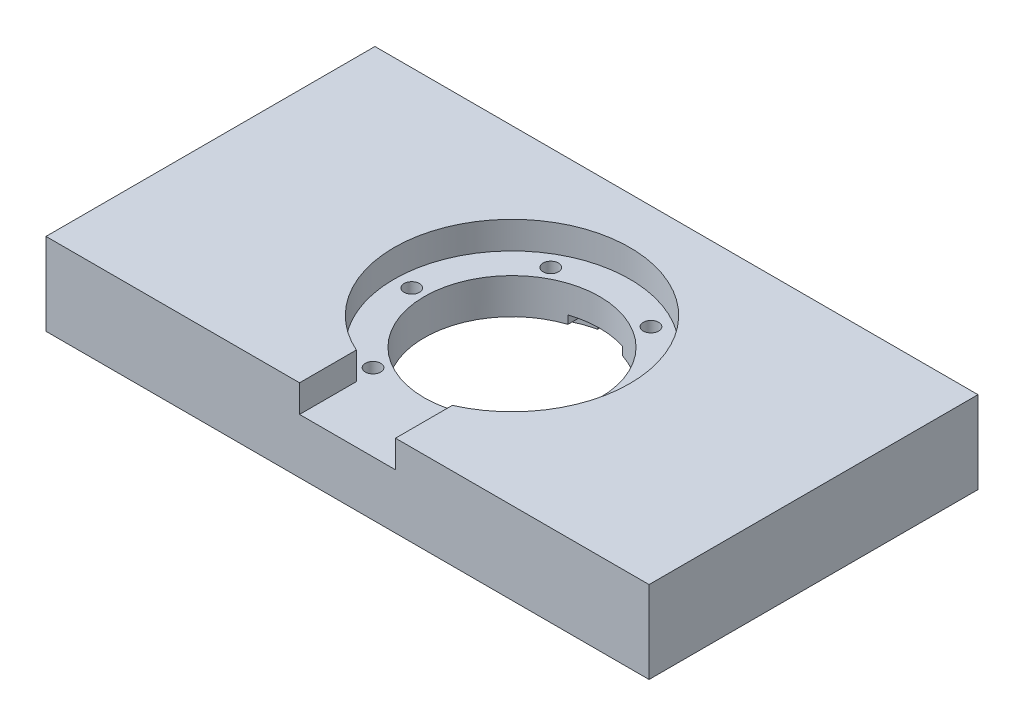
SolidWorks part; units mm, degrees
ref_plane "Front Plane" through (0, 0, 0) normal (0, 0, 1) x (1, 0, 0)
ref_plane "Top Plane" through (0, 0, 0) normal (0, 1, 0) x (1, 0, 0)
ref_plane "Right Plane" through (0, 0, 0) normal (1, 0, 0) x (0, 0, -1)
sketch "Sketch1" plane through (0, 0, 0) normal (0, 1, 0) x (1, 0, 0)
  line L1 (110, -60) -> (-110, -60)
  line L2 (110, -60) -> (110, 60)
  line L3 (110, 60) -> (-110, 60)
  line L4 (-110, -60) -> (-110, 60)
  line L5 (110, -60) -> (-110, 60) construction
  line L6 (110, 60) -> (-110, -60) construction
  circle A0 centre (0, 0) radius 43
  dimension "D1" = 86
  dimension "D2" = 120
  dimension "D3" = 220
extrude "Boss-Extrude1" add sketch "Sketch1" along normal blind 10
sketch "Sketch2" plane through (0, 0, 0) normal (0, -1, 0) x (1, 0, 0)
  line L1 (-110, 60) -> (110, 60)
  line L2 (-110, 60) -> (-110, -60)
  line L3 (-110, -60) -> (110, -60)
  line L4 (110, 60) -> (110, -60)
  circle A0 centre (18.1221, 32.2581) radius 2.8
  circle A1 centre (36.9974, 0.4348) radius 2.8
  circle A2 centre (18.8753, -31.8233) radius 2.8
  circle A3 centre (-18.1221, -32.2581) radius 2.8
  circle A4 centre (-36.9974, -0.4348) radius 2.8
  circle A5 centre (-18.8753, 31.8233) radius 2.8
  point P21 (0, 0)
  dimension "D1" = 5.6
  dimension "D2" = 37
  dimension "D3" = 6
extrude "Boss-Extrude2" add sketch "Sketch2" along normal blind 20
sketch "Sketch3" plane through (0, 0, 60) normal (0, 0, 1) x (1, 0, 0)
  line L0 (-110, 10) -> (110, 10) construction
  line L1 (-17.5, 0) -> (17.5, 0)
  line L2 (-17.5, 0) -> (-17.5, 10)
  line L3 (-17.5, 10) -> (17.5, 10)
  line L4 (17.5, 0) -> (17.5, 10)
  line L5 (-17.5, 0) -> (17.5, 10) construction
  line L6 (-17.5, 10) -> (17.5, 0) construction
  point P0 (0, 5)
  dimension "D1" = 35
  dimension "D2" = 10
extrude "Cut-Extrude1" cut sketch "Sketch3" against normal up to next
sketch "Sketch4" plane through (0, 0, 0) normal (0, 1, 0) x (1, 0, 0)
  circle A0 centre (0, 0) radius 32
  dimension "D1" = 64
extrude "Cut-Extrude2" cut sketch "Sketch4" against normal through all
sketch "Sketch5" plane through (0, 0, -60) normal (0, 0, -1) x (-1, 0, 0)
  line L0 (110, -20) -> (-110, -20) construction
  line L1 (-10, -10) -> (10, -10)
  line L2 (-10, -10) -> (-10, -20)
  line L3 (-10, -20) -> (10, -20)
  line L4 (10, -10) -> (10, -20)
  line L5 (-10, -10) -> (10, -20) construction
  line L6 (-10, -20) -> (10, -10) construction
  point P0 (0, -15)
  dimension "D1" = 20
  dimension "D2" = 10
extrude "Cut-Extrude3" cut sketch "Sketch5" against normal up to next
sketch "Sketch6" plane through (0, -20, 0) normal (0, -1, 0) x (1, 0, 0)
  circle A1 centre (0, 0) radius 42.5
  dimension "D1" = 85
extrude "Cut-Extrude4" cut sketch "Sketch6" against normal blind 7
